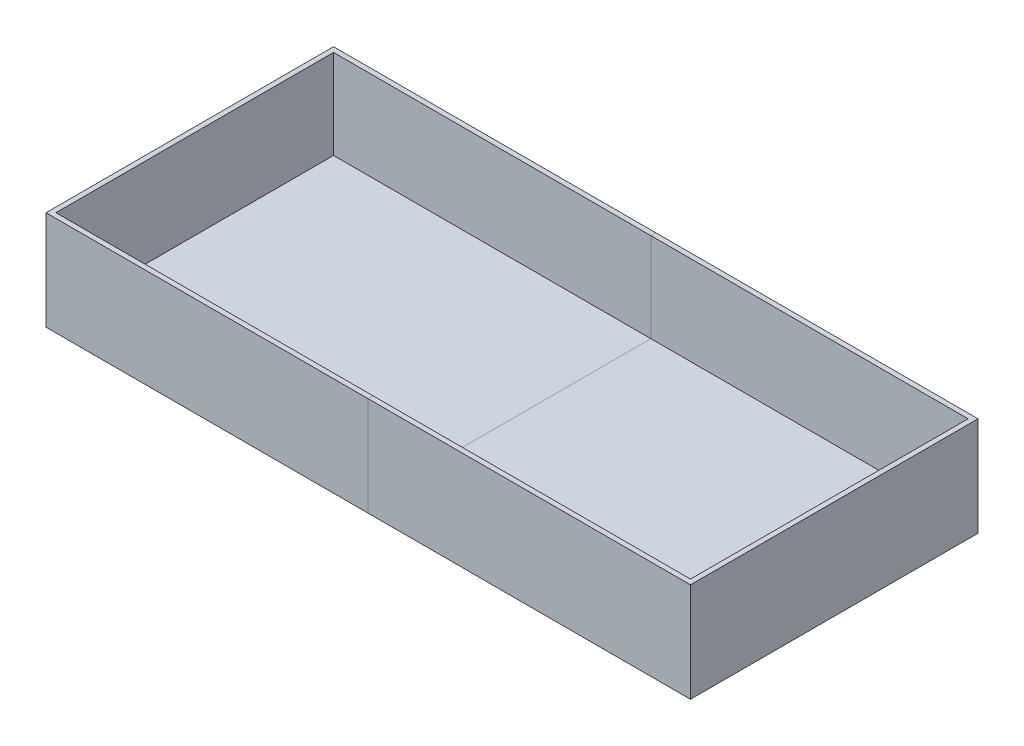
SolidWorks part; units mm, degrees
ref_plane "Front Plane" through (0, 0, 0) normal (0, 0, 1) x (1, 0, 0)
ref_plane "Top Plane" through (0, 0, 0) normal (0, 1, 0) x (1, 0, 0)
ref_plane "Right Plane" through (0, 0, 0) normal (1, 0, 0) x (0, 0, -1)
other "Bounding Box"
ref_plane "Default Plane" through (-206.375, 63.5, -92.075) normal (0, 0, 1) x (1, 0, 0)
sketch "Sketch1" plane through (0, 0, 0) normal (0, 1, 0) x (1, 0, 0)
  line L1 (-203.2, -88.9) -> (203.2, -88.9)
  line L2 (-203.2, -88.9) -> (-203.2, 88.9)
  line L3 (-203.2, 88.9) -> (203.2, 88.9)
  line L4 (203.2, -88.9) -> (203.2, 88.9)
  line L5 (-203.2, -88.9) -> (203.2, 88.9) construction
  line L6 (-203.2, 88.9) -> (203.2, -88.9) construction
  line L7 (-206.375, -92.075) -> (206.375, -92.075)
  line L8 (-206.375, -92.075) -> (-206.375, 92.075)
  line L9 (-206.375, 92.075) -> (206.375, 92.075)
  line L10 (206.375, -92.075) -> (206.375, 92.075)
  line L11 (-206.375, -92.075) -> (206.375, 92.075) construction
  line L12 (-206.375, 92.075) -> (206.375, -92.075) construction
  point P0 (0, 0)
  point P6 (0, 0)
  dimension "D1" = 177.8
  dimension "D2" = 406.4
  dimension "D3" = 184.15
  dimension "D4" = 412.75
sketch "Sketch2" plane through (0, 0, 0) normal (0, 1, 0) x (1, 0, 0)
  line L0 (0, 88.9) -> (0, 0)
  line L1 (-203.2, -88.9) -> (203.2, -88.9)
  line L2 (-203.2, -88.9) -> (-203.2, 88.9)
  line L3 (-203.2, 88.9) -> (203.2, 88.9)
  line L4 (203.2, -88.9) -> (203.2, 88.9)
  line L5 (-203.2, -88.9) -> (203.2, 88.9) construction
  line L6 (-203.2, 88.9) -> (203.2, -88.9) construction
  point P0 (0, 0)
extrude "Boss-Extrude2" add sketch "Sketch1" along normal blind 63.5
ref_plane "Plane2" through (0, 0, 0) normal (1, 0, 0) x (0, 0, -1)
extrude "Boss-Extrude4" add sketch "Sketch2" along normal blind 6.35
split "Split1" trim tools "Plane2" bodies to split 104 resulting bodies 105 106
